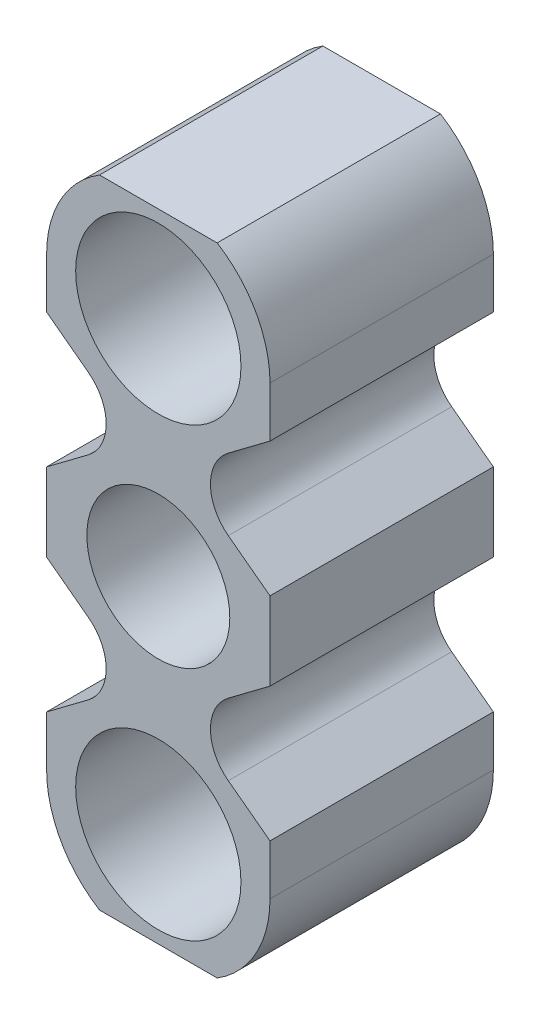
SolidWorks part; units mm, degrees
material "ABS"
ref_plane "Plan de face" through (0, 0, 0) normal (0, 0, 1) x (1, 0, 0)
ref_plane "Plan de dessus" through (0, 0, 0) normal (0, 1, 0) x (1, 0, 0)
ref_plane "Plan de droite" through (0, 0, 0) normal (1, 0, 0) x (0, 0, -1)
sketch "Esquisse1" plane through (0, 0, 0) normal (0, 0, 1) x (1, 0, 0)
  line L0 (0, 0) -> (0, 10) construction
  line L1 (0, 0) -> (0, -10) construction
  line L2 (-5, 10) -> (-5, 2)
  line L3 (-5, 2) -> (-5, -10)
  line L4 (5, 10) -> (5, 0)
  line L5 (5, 0) -> (5, -10)
  circle A0 centre (0, 0) radius 3.2
  circle A1 centre (0, 0) radius 5
  circle A2 centre (0, 10) radius 3.7
  circle A3 centre (0, 10) radius 5
  circle A4 centre (0, -10) radius 3.7
  circle A5 centre (0, -10) radius 5
  point P7 (0, 5)
  point P8 (0, 5)
  dimension "D1" = 6.4
  dimension "D2" = 10
  dimension "D3" = 7.4
  dimension "D4" = 10
  dimension "D5" = 0
extrude "Boss.-Extru.1" add sketch "Esquisse1" along normal blind 10 contours A3 A2 | A3 L2 A1 L4 | A1 A0 | A5 L5 A1 L3 | A5 A4 | A3 A1 L4 | A5 A1 L3
sketch "Esquisse2" plane through (0, 0, 10) normal (0, 0, 1) x (1, 0, 0)
  line L0 (0, 6.3) -> (0, 3.2) construction
  line L1 (0, 4.75) -> (-5, 4.75) construction
  line L2 (-5, 10) -> (-5, -10) construction
  line L3 (0, 4.75) -> (5, 4.75) construction
  line L4 (5, 10) -> (5, -10) construction
  line L5 (5, 7.75) -> (1, 4.75)
  line L6 (1, 4.75) -> (5, 1.75)
  line L7 (5, 1.75) -> (5, 4.75) construction
  line L8 (5, 4.75) -> (5, 7.75) construction
  circle A0 centre (0, 10) radius 3.7 construction
  circle A1 centre (0, 0) radius 3.2 construction
  dimension "D1" = 4
  dimension "D2" = 3
extrude "Enlèv. mat.-Extru.1" cut sketch "Esquisse2" against normal blind 10 and the other way through all
mirror "Symétrie1" about plane through (0, 0, 0) normal (1, 0, 0) of "Enlèv. mat.-Extru.1"
mirror "Symétrie2" about plane through (0, 0, 0) normal (0, 1, 0) of "Symétrie1", "Enlèv. mat.-Extru.1"
fillet "Congé1" radius 2 4 edges at (-1, -4.75, 5) (1, -4.75, 5) (1, 4.75, 5) (-1, 4.75, 5)
sketch "Esquisse3" plane through (0, 0, 0) normal (0, 0, -1) x (-1, 0, 0)
  line L0 (0, -15) -> (0, 15) construction
  line L2 (-8.2194, 14.25) -> (8.2194, 14.25)
  line L3 (-8.2194, 14.25) -> (-8.2194, 15.75)
  line L4 (-8.2194, 15.75) -> (8.2194, 15.75)
  line L5 (8.2194, 14.25) -> (8.2194, 15.75)
  line L6 (-8.2194, 14.25) -> (8.2194, 15.75) construction
  line L7 (-8.2194, 15.75) -> (8.2194, 14.25) construction
  line L8 (-10.5193, -15.75) -> (10.5193, -15.75)
  line L9 (-10.5193, -15.75) -> (-10.5193, -14.25)
  line L10 (-10.5193, -14.25) -> (10.5193, -14.25)
  line L11 (10.5193, -15.75) -> (10.5193, -14.25)
  line L12 (-10.5193, -15.75) -> (10.5193, -14.25) construction
  line L13 (-10.5193, -14.25) -> (10.5193, -15.75) construction
  arc A0 (-5, -10) -> (5, -10) centre (0, -10) ccw construction
  arc A1 (5, 10) -> (-5, 10) centre (0, 10) ccw construction
  dimension "D1" = 1.5
extrude "Enlèv. mat.-Extru.2" cut sketch "Esquisse3" against normal through all
equation "\"entretoiseBearing\"= 1.5mm"
equation "\"length_tibia\"= 206mm"
equation "\"length_femur\"= 117mm"
equation "\"length_coxa\"= 27mm"
equation "\"height\"= 40mm"
equation "\"width\"= 100mm"
equation "\"lever\"= 40mm"
equation "\"errorFlat\"= 0.20mm"
equation "\"errorFlat_tight\"= 0.15mm"
equation "\"errorCircle\"= 0.40mm"
equation "\"errorCircle_tight\" = 0.30mm"
equation "\"cuticule\"=1.5mm"
equation "\"cuticule_attach_w\"=10mm"
equation "\"cuticule_attach_h\"=2.5mm"
equation "\"depthMagnet\"= 1mm"
equation "\"insert_d\" = 3.2mm"
equation "\"insert_l\" = 5mm"
equation "\"D3@Esquisse1\"= 7 + \"errorCircle\""
equation "\"D1@Esquisse1\"= 6 + \"errorCircle\""
